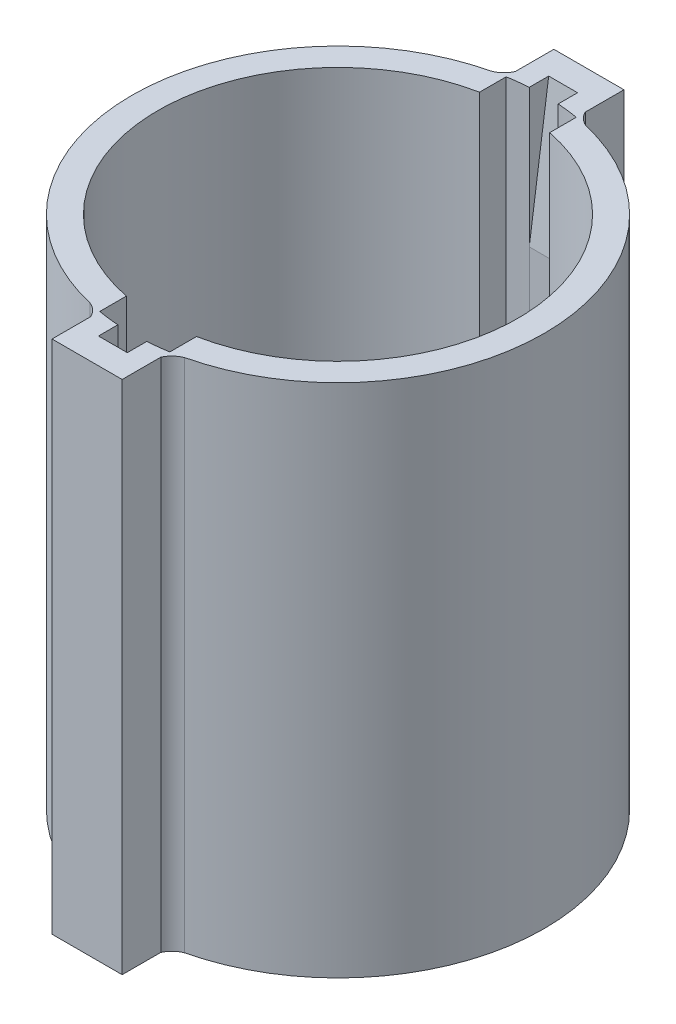
SolidWorks part; units mm, degrees
ref_plane "Front Plane" through (0, 0, 0) normal (0, 0, 1) x (1, 0, 0)
ref_plane "Top Plane" through (0, 0, 0) normal (0, 1, 0) x (1, 0, 0)
ref_plane "Right Plane" through (0, 0, 0) normal (1, 0, 0) x (0, 0, -1)
sketch "Sketch1" plane through (0, 0, 0) normal (0, 1, 0) x (1, 0, 0)
  line L0 (52.6654, 3.4215) -> (50.1865, -10.738)
  line L1 (-1.4, 21.835) -> (1.4, 21.835)
  line L2 (-1.4, 21.835) -> (-1.4, -21.835)
  line L3 (-1.4, -21.835) -> (1.4, -21.835)
  line L4 (1.4, 21.835) -> (1.4, -21.835)
  line L5 (-1.4, 21.835) -> (1.4, -21.835) construction
  line L6 (-1.4, -21.835) -> (1.4, 21.835) construction
  line L7 (-3.4, 24.335) -> (3.4, 24.335)
  line L8 (-3.4, 24.335) -> (-3.4, -24.335)
  line L9 (-3.4, -24.335) -> (3.4, -24.335)
  line L10 (3.4, 24.335) -> (3.4, -24.335)
  line L11 (-3.4, 24.335) -> (3.4, -24.335) construction
  line L12 (-3.4, -24.335) -> (3.4, 24.335) construction
  line L13 (52.6654, 3.4215) -> (68.8521, 0.5877)
  line L14 (0, 0) -> (0, 0.7466) construction
  line L15 (0, 0) -> (-0.4499, 0) construction
  circle A0 centre (0, 0) radius 17.46
  circle A1 centre (0, 0) radius 20
  arc A2 (-3.4, 20.5901) -> (-4.5986, 19.4641) centre (-5.3754, 21.492) cw
  arc A3 (3.4, 20.5901) -> (4.5986, 19.4641) centre (5.3754, 21.492) ccw
  arc A4 (3.4, -20.5901) -> (4.5986, -19.4641) centre (5.3754, -21.492) cw
  arc A5 (-3.4, -20.5901) -> (-4.5986, -19.4641) centre (-5.3754, -21.492) ccw
  dimension "D1" = 34.92
  dimension "D4" = 40
  dimension "D2" = 2.8
  dimension "D3" = 43.67
  dimension "D5" = 6.8
  dimension "D6" = 48.67
  dimension "D7" = 14.3748
  dimension "D8" = 90
extrude "Boss-Extrude1" add sketch "Sketch1" along normal blind 50
sketch "Sketch2" plane through (-1.4, 0, 0) normal (1, 0, 0) x (0, 0, -1)
  line L0 (21.835, 50) -> (14.6492, -1.1295)
  line L1 (21.835, 50) -> (25.891, 50)
  line L2 (24.335, 50) -> (20.5901, 50) construction
  line L3 (21.835, 50) -> (21.835, 0)
  line L4 (24.335, 0) -> (20.5901, 0) construction
  line L5 (21.835, 0) -> (14.808, 0)
  line L6 (0, 0) -> (0, 7.408)
  line L7 (21.835, 50) -> (21.835, 0)
  line L8 (-21.835, 0) -> (-14.808, 0)
  line L9 (-21.835, 50) -> (-21.835, 0)
  line L10 (-21.835, 50) -> (-14.6492, -1.1295)
  dimension "D1" = 82
extrude "Boss-Extrude2" add sketch "Sketch2" along normal blind 2.8 contours L4 L0 L2 | L10 L9 L8
sketch "Sketch3" plane through (0, 0, 0) normal (0, -1, 0) x (1, 0, 0)
  line L0 (-1.4, 19.9509) -> (-1.4, 14.808)
  line L1 (-1.4, 14.808) -> (1.4, 14.808)
  line L2 (1.4, 14.808) -> (1.4, 19.9509)
  circle A0 centre (0, 0) radius 20
  line M8 (-1.4, 19.9509) -> (-1.4, 14.808)
  line M9 (-1.4, 14.808) -> (1.4, 14.808)
  line M10 (1.4, 14.808) -> (1.4, 19.9509)
extrude "Cut-Extrude1" cut sketch "Sketch3" against normal through all both contours A0 M10 M8 M9
